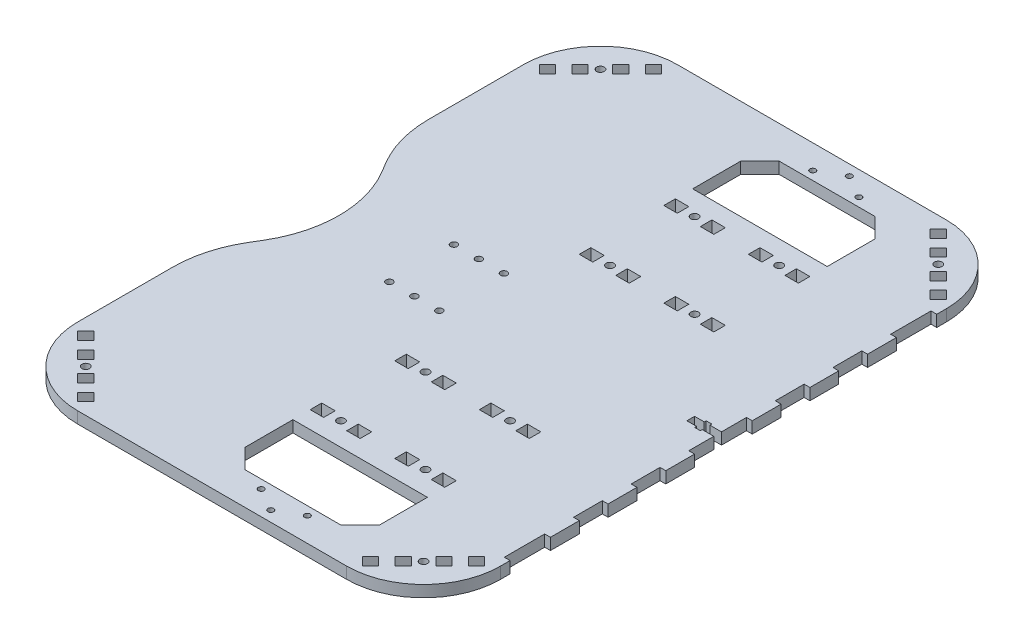
SolidWorks part; units mm, degrees
material "Balsa"
ref_plane "Plan de face" through (0, 0, 0) normal (0, 0, 1) x (1, 0, 0)
ref_plane "Plan de dessus" through (0, 0, 0) normal (0, 1, 0) x (1, 0, 0)
ref_plane "Plan de droite" through (0, 0, 0) normal (1, 0, 0) x (0, 0, -1)
sketch "Esquisse1" plane through (0, 0, 0) normal (0, 1, 0) x (1, 0, 0)
  line L0 (-70.754, -70.754) -> (149.246, -70.754)
  line L1 (149.246, -70.754) -> (149.246, 241.246)
  line L2 (-70.754, 241.246) -> (-70.754, -70.754)
  line L3 (149.246, 241.246) -> (-70.754, 241.246)
  dimension "D1" = 312
  dimension "D2" = 220
extrude "Boss.-Extru.1" add sketch "Esquisse1" along normal blind 6
ref_plane "Plan1" through (0, 0, -85.246) normal (0, 0, 1) x (1, 0, 0)
sketch "Esquisse2" plane through (0, 6, 0) normal (0, 1, 0) x (1, 0, 0)
  line L0 (92.246, 177.246) -> (80.246, 177.246) construction
  line L1 (99.246, 180.246) -> (92.246, 180.246)
  line L2 (99.246, 180.246) -> (99.246, 174.246)
  line L3 (99.246, 174.246) -> (92.246, 174.246)
  line L4 (92.246, 180.246) -> (92.246, 174.246)
  line L5 (80.246, 174.246) -> (73.246, 174.246)
  line L6 (80.246, 174.246) -> (80.246, 180.246)
  line L7 (80.246, 180.246) -> (73.246, 180.246)
  line L8 (73.246, 174.246) -> (73.246, 180.246)
  line L9 (55.246, 174.246) -> (48.246, 174.246)
  line L10 (55.246, 174.246) -> (55.246, 180.246)
  line L11 (55.246, 180.246) -> (48.246, 180.246)
  line L12 (48.246, 174.246) -> (48.246, 180.246)
  line L13 (36.246, 174.246) -> (29.246, 174.246)
  line L14 (36.246, 174.246) -> (36.246, 180.246)
  line L15 (36.246, 180.246) -> (29.246, 180.246)
  line L16 (29.246, 174.246) -> (29.246, 180.246)
  line L17 (48.246, 177.246) -> (36.246, 177.246) construction
  line L18 (-70.754, 241.246) -> (-70.754, -70.754) construction
  line L19 (-70.754, 241.246) -> (-70.754, -70.754) construction
  circle A0 centre (86.246, 177.246) radius 2
  circle A1 centre (42.246, 177.246) radius 2
  point P27 (-70.754, 85.246)
  dimension "D9" = 4
  dimension "D10" = 4
  dimension "D1" = 7
  dimension "D2" = 7
  dimension "D3" = 7
  dimension "D4" = 7
  dimension "D5" = 12
  dimension "D6" = 12
  dimension "D7" = 18
  dimension "D8" = 6
  dimension "D11" = 89
  dimension "D12" = 100
extrude "Enlèv. mat.-Extru.1" cut sketch "Esquisse2" against normal through all
sketch "Esquisse3" plane through (0, 6, 0) normal (0, 1, 0) x (1, 0, 0)
  line L0 (99.246, 180.246) -> (92.246, 180.246) construction
  line L1 (99.246, 189.246) -> (29.246, 189.246)
  line L2 (99.246, 189.246) -> (99.246, 224.246)
  line L3 (99.246, 224.246) -> (29.246, 224.246)
  line L4 (29.246, 189.246) -> (29.246, 224.246)
  line L5 (99.246, 174.246) -> (99.246, 180.246) construction
  line L6 (29.246, 180.246) -> (29.246, 174.246) construction
  dimension "D1" = 9
  dimension "D2" = 35
extrude "Enlèv. mat.-Extru.2" cut sketch "Esquisse3" against normal through all
pattern_linear "Répétition linéaire1" count 2 spacing 44 along (0, 0, 1) of "Enlèv. mat.-Extru.1"
sketch "Esquisse4" plane through (0, 6, 0) normal (0, 1, 0) x (1, 0, 0)
  line L1 (99.246, 224.246) -> (29.246, 224.246) construction
  line L7 (64.246, 224.246) -> (64.246, 283.1189) construction
  line L8 (52.246, 228.746) -> (76.246, 228.746) construction
  circle A0 centre (52.246, 228.746) radius 1.5
  circle A1 centre (64.246, 235.746) radius 1.5
  circle A2 centre (76.246, 228.746) radius 1.5
  dimension "D5" = 3
  dimension "D6" = 3
  dimension "D7" = 3
  dimension "D2" = 4.5
  dimension "D3" = 7
  dimension "D9" = 12
  dimension "D10" = 12
extrude "Enlèv. mat.-Extru.3" cut sketch "Esquisse4" against normal through all
chamfer "Chanfrein1" distance 10 angle 45 2 edges at (99.246, 3, -224.246) (29.246, 3, -224.246)
mirror "Symétrie1" about plane through (0, 0, -85.246) normal (0, 0, 1) of "Chanfrein1", "Enlèv. mat.-Extru.2", "Répétition linéaire1", "Enlèv. mat.-Extru.1", "Enlèv. mat.-Extru.3"
fillet "Congé1" radius 40 4 edges at (149.246, 3, 70.754) (149.246, 3, -241.246) (-70.754, 3, -241.246) (-70.754, 3, 70.754)
sketch "Esquisse5" plane through (0, 6, 0) normal (0, 1, 0) x (1, 0, 0)
  line L0 (-70.754, 85.246) -> (83.5531, 85.246) construction
  line L1 (-70.754, 201.246) -> (-70.754, -30.754) construction
  line L2 (-7.754, 102.046) -> (18.246, 102.046) construction
  line L3 (18.246, 68.446) -> (-7.754, 68.446) construction
  line L4 (-7.754, 102.046) -> (-7.754, 68.446) construction
  circle A0 centre (18.246, 102.046) radius 1.75
  circle A1 centre (5.246, 102.046) radius 1.75
  circle A2 centre (-7.754, 102.046) radius 1.75
  circle A3 centre (18.246, 68.446) radius 1.75
  circle A4 centre (5.246, 68.446) radius 1.75
  circle A5 centre (-7.754, 68.446) radius 1.75
  dimension "D6" = 3.5
  dimension "D7" = 3.5
  dimension "D8" = 3.5
  dimension "D9" = 3.5
  dimension "D10" = 3.5
  dimension "D11" = 3.5
  dimension "D1" = 33.6
  dimension "D2" = 16.8
  dimension "D3" = 26
  dimension "D4" = 26
  dimension "D5" = 63
extrude "Enlèv. mat.-Extru.4" cut sketch "Esquisse5" against normal through all
sketch "Esquisse6" plane through (0, 6, 0) normal (0, 1, 0) x (1, 0, 0)
  line L0 (-30.754, -70.754) -> (-70.754, -30.754) construction
  line L1 (-50.754, -50.754) -> (-30.0091, -30.0091) construction
  line L2 (-53.936, -47.572) -> (-58.1786, -43.3294)
  line L3 (-53.936, -47.572) -> (-49.6934, -43.3294)
  line L4 (-58.1786, -43.3294) -> (-53.936, -39.0868)
  line L5 (-49.6934, -43.3294) -> (-53.936, -39.0868)
  line L6 (-62.4213, -39.0868) -> (-66.6639, -34.8441)
  line L7 (-62.4213, -39.0868) -> (-58.1786, -34.8441)
  line L8 (-66.6639, -34.8441) -> (-62.4213, -30.6015)
  line L9 (-58.1786, -34.8441) -> (-62.4213, -30.6015)
  line L10 (-47.572, -53.936) -> (-43.3294, -58.1786)
  line L11 (-47.572, -53.936) -> (-43.3294, -49.6934)
  line L12 (-43.3294, -58.1786) -> (-39.0868, -53.936)
  line L13 (-43.3294, -49.6934) -> (-39.0868, -53.936)
  line L14 (-39.0868, -62.4213) -> (-34.8441, -66.6639)
  line L15 (-39.0868, -62.4213) -> (-34.8441, -58.1786)
  line L16 (-34.8441, -66.6639) -> (-30.6015, -62.4213)
  line L17 (-34.8441, -58.1786) -> (-30.6015, -62.4213)
  line L18 (-51.8147, -45.4507) -> (-45.4507, -51.8147) construction
  circle A0 centre (-48.6327, -48.6327) radius 2
  dimension "D9" = 4
  dimension "D1" = 6
  dimension "D2" = 6
  dimension "D3" = 6
  dimension "D4" = 6
  dimension "D5" = 6
  dimension "D6" = 6
  dimension "D7" = 6
  dimension "D8" = 9
extrude "Enlèv. mat.-Extru.5" cut sketch "Esquisse6" against normal blind 6
mirror "Symétrie2" about plane through (0, 0, -85.246) normal (0, 0, 1) of "Enlèv. mat.-Extru.5"
ref_plane "Plan2" through (39.246, 0, 0) normal (1, 0, 0) x (0, 0, -1)
mirror "Symétrie3" about plane through (39.246, 0, 0) normal (1, 0, 0) of "Symétrie2", "Enlèv. mat.-Extru.5"
sketch "Esquisse7" plane through (0, 6, 0) normal (0, 1, 0) x (1, 0, 0)
  line L0 (149.246, 85.246) -> (106.1276, 85.246) construction
  line L1 (149.246, -30.754) -> (149.246, 201.246) construction
  line L2 (146.246, -28.2713) -> (146.246, 195.0304) construction
  line L3 (137.246, 87.246) -> (137.246, 88.246)
  line L4 (146.246, 100.246) -> (149.246, 100.246)
  line L5 (146.246, 100.246) -> (146.246, 87.246)
  line L6 (146.246, 70.246) -> (149.246, 70.246)
  line L7 (149.246, 100.246) -> (149.246, 70.246)
  line L8 (146.246, 115.246) -> (149.246, 115.246)
  line L9 (146.246, 115.246) -> (146.246, 130.246)
  line L10 (146.246, 130.246) -> (149.246, 130.246)
  line L11 (149.246, 115.246) -> (149.246, 130.246)
  line L12 (146.246, 145.246) -> (149.246, 145.246)
  line L13 (146.246, 145.246) -> (146.246, 160.246)
  line L14 (146.246, 160.246) -> (149.246, 160.246)
  line L15 (149.246, 145.246) -> (149.246, 160.246)
  line L16 (146.246, 175.246) -> (149.246, 175.246)
  line L17 (146.246, 175.246) -> (146.246, 196.246)
  line L18 (146.246, 196.246) -> (149.246, 196.246)
  line L19 (149.246, 175.246) -> (149.246, 196.246)
  line L20 (146.246, 55.246) -> (149.246, 55.246)
  line L21 (146.246, 55.246) -> (146.246, 40.246)
  line L22 (146.246, 40.246) -> (149.246, 40.246)
  line L23 (149.246, 55.246) -> (149.246, 40.246)
  line L24 (146.246, 25.246) -> (149.246, 25.246)
  line L25 (146.246, 25.246) -> (146.246, 10.246)
  line L26 (146.246, 10.246) -> (149.246, 10.246)
  line L27 (149.246, 25.246) -> (149.246, 10.246)
  line L28 (146.246, -4.754) -> (149.246, -4.754)
  line L29 (146.246, -4.754) -> (146.246, -25.754)
  line L30 (146.246, -25.754) -> (149.246, -25.754)
  line L31 (149.246, -4.754) -> (149.246, -25.754)
  line L32 (146.246, 87.246) -> (140.246, 87.246)
  line L34 (146.246, 83.246) -> (140.246, 83.246)
  line L35 (146.246, 83.246) -> (146.246, 70.246)
  line L36 (140.246, 82.246) -> (137.246, 82.246)
  line L37 (140.246, 82.246) -> (140.246, 83.246)
  line L38 (140.246, 88.246) -> (137.246, 88.246)
  line L39 (137.246, 82.246) -> (137.246, 83.246)
  line L40 (137.246, 87.246) -> (132.246, 87.246)
  line L41 (140.246, 87.246) -> (140.246, 88.246)
  line L42 (137.246, 83.246) -> (132.246, 83.246)
  line L43 (132.246, 87.246) -> (132.246, 83.246)
  dimension "D1" = 3
  dimension "D2" = 15
  dimension "D3" = 15
  dimension "D4" = 15
  dimension "D5" = 15
  dimension "D6" = 15
  dimension "D7" = 15
  dimension "D8" = 21
  dimension "D9" = 15
  dimension "D10" = 15
  dimension "D11" = 15
  dimension "D12" = 15
  dimension "D13" = 15
  dimension "D14" = 15
  dimension "D15" = 21
  dimension "D16" = 6
  dimension "D17" = 3
  dimension "D18" = 5
  dimension "D19" = 4
  dimension "D20" = 1
extrude "Enlèv. mat.-Extru.6" cut sketch "Esquisse7" against normal blind 6
sketch "Esquisse8" plane through (0, 6, 0) normal (0, 1, 0) x (1, 0, 0)
  line L0 (-70.754, 85.246) -> (65.3944, 85.246) construction
  line L1 (-70.754, 201.246) -> (-70.754, -30.754) construction
  line L2 (-70.754, 135.246) -> (-40.754, 85.246)
  line L3 (-40.754, 85.246) -> (-70.754, 35.246)
  line L4 (-70.754, 135.246) -> (-70.754, 35.246)
  dimension "D1" = 50
  dimension "D2" = 50
  dimension "D3" = 30
extrude "Enlèv. mat.-Extru.7" cut sketch "Esquisse8" against normal blind 6
fillet "Congé2" radius 60 3 edges at (-70.754, 3, -35.246) (-40.754, 3, -85.246) (-70.754, 3, -135.246)
